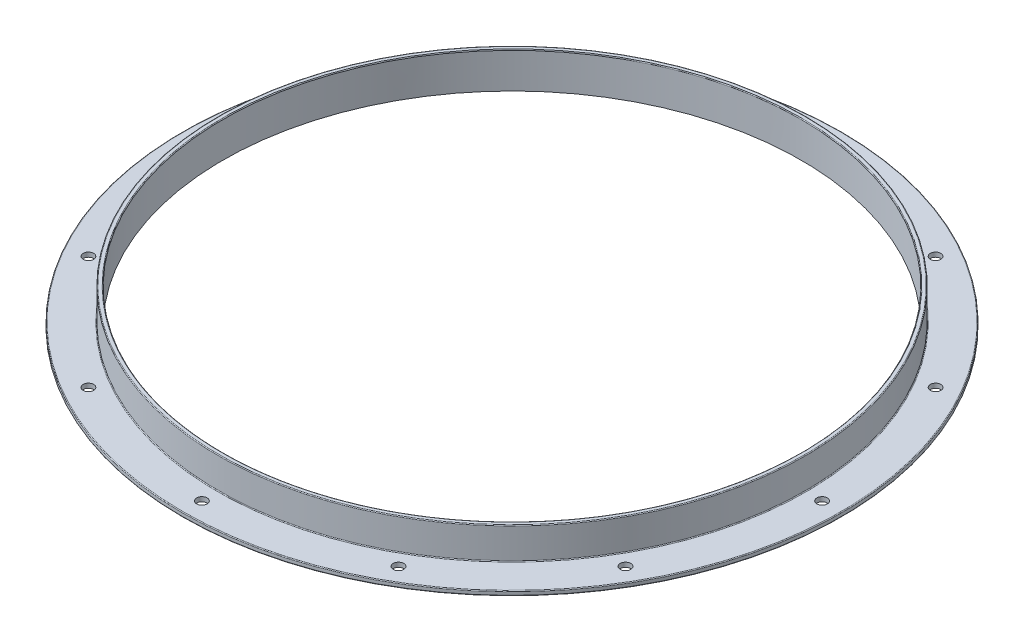
SolidWorks part; units mm, degrees
ref_plane "Front Plane" through (0, 0, 0) normal (0, 0, 1) x (1, 0, 0)
ref_plane "Top Plane" through (0, 0, 0) normal (0, 1, 0) x (1, 0, 0)
ref_plane "Right Plane" through (0, 0, 0) normal (1, 0, 0) x (0, 0, -1)
sketch "Sketch1" plane through (0, 0, 0) normal (1, 0, 0) x (0, 0, -1)
  line L0 (306.3875, 0) -> (349.25, 0)
  line L1 (349.25, 0) -> (349.25, 4.7625)
  line L2 (349.25, 4.7625) -> (311.15, 4.7625)
  line L3 (311.15, 4.7625) -> (311.15, 38.1)
  line L4 (311.15, 38.1) -> (306.3875, 38.1)
  line L5 (0, 38.1) -> (0, 0) construction
  line L6 (0, 50.5185) -> (0, -6.35) construction
  line L7 (306.3875, 38.1) -> (306.3875, 0)
  dimension "Flange Thk" = 4.7625
  dimension "Depth" = 38.1
  dimension "Flange Ht" = 38.1
  dimension "D1" = 4.7625
  dimension "D2" = 6.35
  dimension "ID" = 612.775
revolve "Revolve1" add sketch "Sketch1" angle 360 about L5
sketch "Sketch2" plane through (0, 38.1, 0) normal (0, 1, 0) x (1, 0, 0)
  line L0 (12.7, 0) -> (311.15, 0) construction
  circle A0 centre (0, 0) radius 115.8875
  circle A2 centre (0, 0) radius 349.25 construction
  circle A4 centre (0, 0) radius 311.15 construction
  dimension "D1" = 298.45
  dimension "ID" = 231.775
fillet "Fillet3" radius 0.7938 2 edges at (0, 0, 349.25) (0, 4.7625, 349.25)
fillet "Fillet4" radius 0.7938 3 edges at (0, 38.1, 311.15) (0, 4.7625, 311.15) (0, 38.1, 306.3875)
sketch "Sketch3" plane through (0, 4.7625, 0) normal (0, 1, 0) x (-1, 0, 0)
  circle A0 centre (0, -328.6125) radius 5.5563
  circle A1 centre (0, 0) radius 328.6125 construction
  dimension "mounting hole size" = 11.1125
  dimension "BoltCircle" = 657.225
extrude "Cut-Extrude1" cut sketch "Sketch3" against normal through all
pattern_circular "CirPattern1" count 12 over 360 about axis through (0, 0, 0) along (0, 1, 0) of "Cut-Extrude1"
equation "\"D1@Fillet3\" = \"Flange Thk@Sketch1\"/6"
equation "\"D1@Fillet4\" = \"Flange Thk@Sketch1\"/6"
equation "\"D1@Sketch1\" = \"Flange Thk@Sketch1\""
